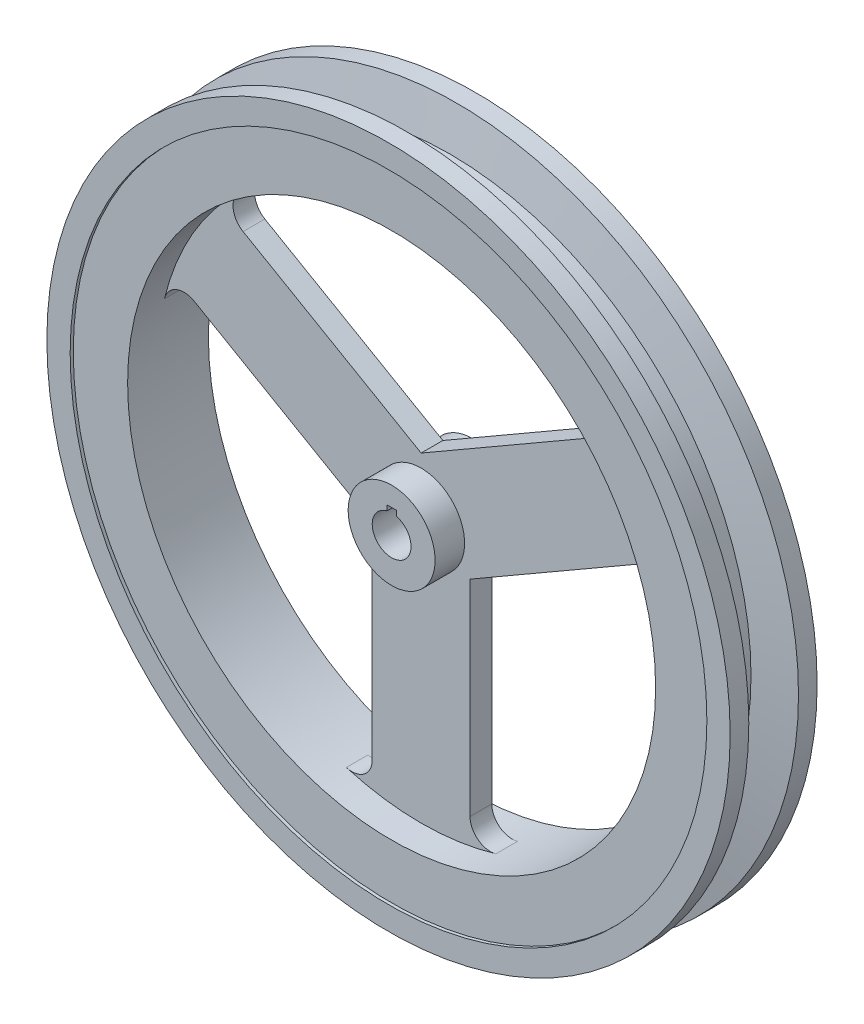
SolidWorks part; units mm, degrees
ref_plane "前视基准面" through (0, 0, 0) normal (0, 0, 1) x (1, 0, 0)
ref_plane "上视基准面" through (0, 0, 0) normal (0, 1, 0) x (1, 0, 0)
ref_plane "右视基准面" through (0, 0, 0) normal (1, 0, 0) x (0, 0, -1)
sketch "草图2" plane through (0, 0, 0) normal (1, 0, 0) x (0, 0, -1)
  line L0 (0, 123.3333) -> (0, 85) construction
  line L1 (-67.9167, 0) -> (56.6667, 0) construction
  line L2 (14, 102.5) -> (14, 110)
  line L3 (14, 110) -> (8, 110)
  line L4 (8, 110) -> (5.7077, 97)
  line L5 (5.7077, 97) -> (-5.7077, 97)
  line L6 (14, 102.5) -> (13, 102.5)
  line L7 (13, 102.5) -> (13, 85)
  line L8 (-14, 102.5) -> (-13, 102.5)
  line L9 (-14, 102.5) -> (-14, 110)
  line L10 (-14, 110) -> (-8, 110)
  line L11 (-8, 110) -> (-5.7077, 97)
  line L12 (-13, 102.5) -> (-13, 85)
  line L13 (13, 85) -> (-13, 85)
  line L14 (0, 0) -> (0, -87.5) construction
  point P18 (0, 97)
  dimension "D1" = 110
  dimension "D2" = 10
  dimension "D3" = 97
  dimension "D4" = 8
  dimension "D5" = 14
  dimension "D6" = 13
  dimension "D8" = 85
revolve "旋转1" add sketch "草图2" angle 360 about L1
sketch "草图3" plane through (0, 0, 0) normal (0, 0, 1) x (1, 0, 0)
  line L0 (0, 0) -> (0, 53.4617) construction
  line L1 (0, 18.1865) -> (-64.4624, 55.4039)
  line L2 (0, 0) -> (-62.5781, -36.1295) construction
  line L3 (-15.75, -9.0933) -> (-80.2124, 28.1241)
  line L4 (15.75, -9.0933) -> (80.2124, 28.1241)
  line L5 (0, 18.1865) -> (64.4624, 55.4039)
  line L6 (-15.75, -9.0933) -> (-15.75, -83.5281)
  line L7 (15.75, -9.0933) -> (15.75, -83.5281)
  circle A1 centre (0, 0) radius 85 construction
  arc A5 (-80.2124, 28.1241) -> (-64.4624, 55.4039) centre (0, 0) cw
  arc A6 (64.4624, 55.4039) -> (80.2124, 28.1241) centre (0, 0) cw
  arc A7 (-15.75, -83.5281) -> (15.75, -83.5281) centre (0, 0) ccw
  dimension "D2" = 60
  dimension "D3" = 120
  dimension "D4" = 31.5
  dimension "D5" = 3
extrude "凸台-拉伸1" add sketch "草图3" along normal mid plane 7
fillet "圆角1" radius 6.5 6 edges at (-15.75, -83.5281, 0) (15.75, -83.5281, 0) (-80.2124, 28.1241, 0) (-64.4624, 55.4039, 0) (64.4624, 55.4039, 0) (80.2124, 28.1241, 0)
sketch "草图4" plane through (0, 0, 0) normal (0, 0, 1) x (1, 0, 0)
  circle A0 centre (0, 0) radius 14
  dimension "D1" = 28
extrude "凸台-拉伸2" add sketch "草图4" along normal mid plane 26
sketch "草图5" plane through (0, 0, 0) normal (0, 0, 1) x (1, 0, 0)
  line L0 (-1.5, 6.0673) -> (-1.5, 7.75)
  line L1 (-1.5, 7.75) -> (1.5, 7.75)
  line L2 (1.5, 7.75) -> (1.5, 6.0673)
  arc A0 (-1.5, 6.0673) -> (1.5, 6.0673) centre (0, 0) ccw
  dimension "D1" = 12.5
  dimension "D2" = 3
  dimension "D3" = 7.75
extrude "切除-拉伸1" cut sketch "草图5" against normal mid plane 26 contours A0 L2 L1 L0
